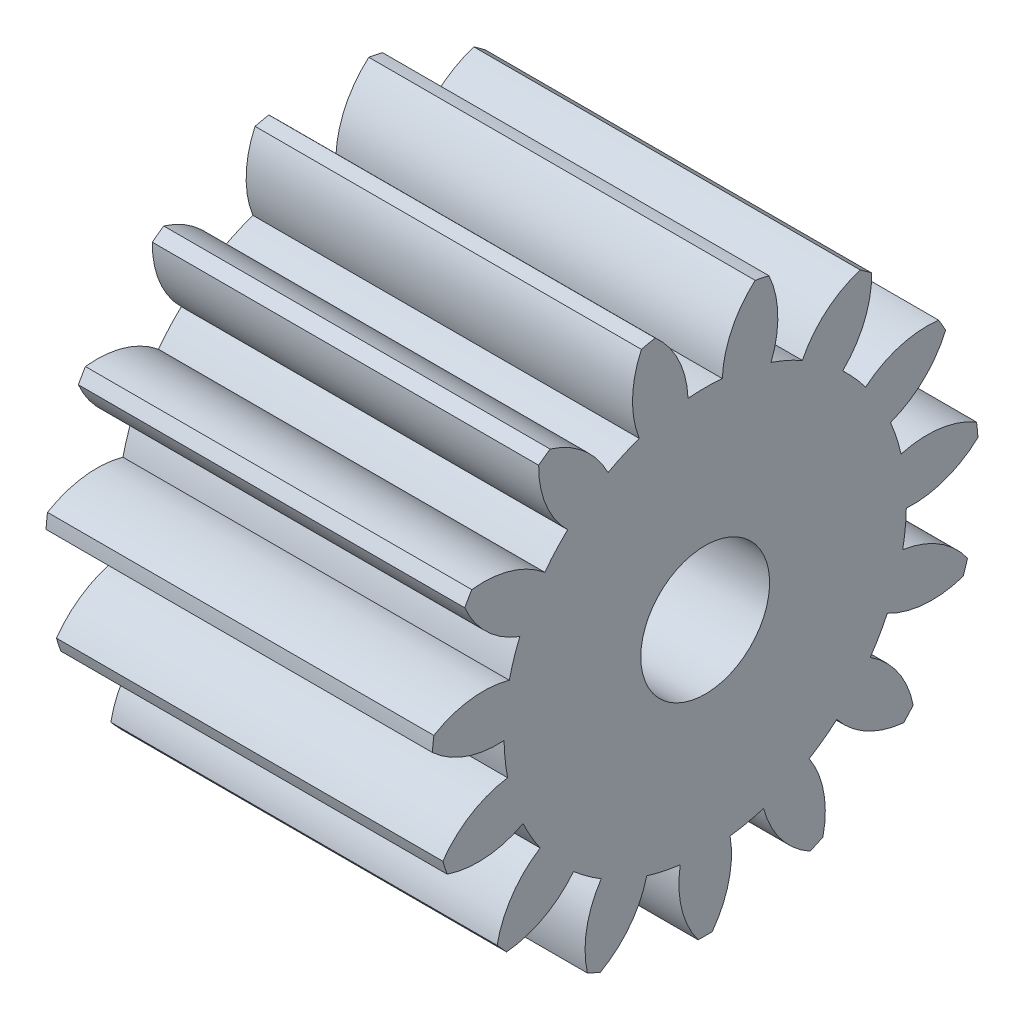
SolidWorks part; units mm, degrees
ref_plane "Plane1" through (0, 0, 0) normal (0, 0, 1) x (1, 0, 0)
ref_plane "Plane2" through (0, 0, 0) normal (0, 1, 0) x (1, 0, 0)
ref_plane "Plane3" through (0, 0, 0) normal (1, 0, 0) x (0, 0, -1)
sketch "HoldingSke" plane through (0, 0, 0) normal (0, 1, 0) x (1, 0, 0)
  line L0 (0, 0) -> (1.9319, -0.5176)
  line L1 (-15, 0) -> (100, 0) construction
  line L2 (0, 0) -> (-2.1039, 2.3779)
  line L3 (0, 0) -> (-11.863, 4.5341)
  line L4 (0, 0) -> (8.3417, 2.2352)
  line L5 (0, 0) -> (-46.8476, -17.4728)
  line L6 (0, 0) -> (-4.9738, -3.3558)
  line L7 (-2.1039, 2.3779) -> (8.6586, 51.2059)
  line L8 (-76.2, 54.61) -> (-75.9, 54.61)
  line L9 (-71.009, 38.7566) -> (-53.1078, 45.2721)
  line L10 (-76.2, 71.12) -> (104.1128, 71.12)
  line L11 (0, 0) -> (-6, 0)
  line L12 (-76.2, 101.6) -> (-76.181, 101.6)
  line L13 (24.9733, 27.94) -> (52.9518, 28.4284)
  line L14 (24.9733, 27.94) -> (24.9743, 27.94)
  line L15 (24.9733, 27.94) -> (100.4006, 29.5858)
  line L16 (-63.627, -0.5) -> (-12.827, -0.5)
  circle A0 centre (0, 0) radius 1
  circle A1 centre (0, 0) radius 3.124
  circle A2 centre (0, 0) radius 37.5
  circle A3 centre (0, 0) radius 1
  dimension "MHD" = 6.248
  dimension "Hub_dia" = 75
  dimension "Bore" = 2
  dimension "MBD" = 2
  dimension "Num_teeth" = 15
  dimension "Pitch" = 2
  dimension "Overall_len" = 50
  dimension "Show_teeth" = 15
  dimension "Thickness" = 6
  dimension "OAL" = 50.0001
  dimension "T_dim" = 0.3
  dimension "Ap" = 20
  dimension "H" = 19.05
  dimension "Pitch_radius" = 180.3128
  dimension "Width" = 6
  dimension "Backlash" = 0.019
  dimension "Addendum_fac" = 1
  dimension "Dedendum_fac" = 1.25
  dimension "Clearance_fac" = 0.25
  dimension "Dedendum_add" = 0.001
  dimension "Module" = 0.5
sketch "BasProSke" plane through (0, 0, 0) normal (0, 1, 0) x (1, 0, 0)
  line L0 (-10, 0) -> (60, 0) construction
  line L1 (0, 0) -> (0, 4.25)
  line L2 (0, 0) -> (6, 0)
  line L3 (6, 0) -> (6, 4.25)
  line L4 (6, 4.25) -> (0, 4.25)
  dimension "Thickness" = 6
  dimension "Diameter" = 8.5
revolve "Base-Revolve" add sketch "BasProSke" angle 360 about L0
sketch "TooCutSke" plane through (0, 0, 0) normal (1, 0, 0) x (0, 0, -1)
  line L1 (0, 0) -> (0, 107) construction
  line L2 (0, 0) -> (-0.4252, 3.7258) construction
  line L3 (0, 0) -> (-1.5522, 7.3025) construction
  line L4 (-0.4252, 3.7258) -> (-0.7761, 3.6512) construction
  arc A0 (0.2658, 3.1127) -> (-0.2658, 3.1127) centre (0, 0) ccw
  arc A1 (0.8008, 4.1997) -> (-0.8008, 4.1997) centre (0, 0) ccw
  circle A2 centre (0, 0) radius 3.75 construction
  circle A3 centre (0, 0) radius 3.5238 construction
  arc A4 (-0.2658, 3.1127) -> (-0.8008, 4.1997) centre (-1.7645, 3.0503) ccw
  arc A5 (0.8008, 4.1997) -> (0.2658, 3.1127) centre (1.7645, 3.0503) ccw
  dimension "Root_dia" = 6.248
  dimension "Overcut_dia" = 8.5508
  dimension "Pitch_dia" = 7.5
  dimension "Base_dia" = 7.0477
  dimension "Flank_rad" = 1.5
  dimension "Half_ang" = 12
  dimension "Half_CT" = 0.3587
extrude "ToothCut" cut sketch "TooCutSke" along normal through all
fillet "Breaks" [suppressed] radius 0.01
fillet "RootFillets" [suppressed] radius 0.126
pattern_circular "TeethCuts" count 15 every 24 about axis through (-10, 0, 0) along (1, 0, 0) of "ToothCut", "RootFillets", "Breaks"
sketch "HubNeaOneSke" plane through (0, 0, 0) normal (-1, 0, 0) x (0, 0, 1)
  circle A0 centre (0, 0) radius 3.124
  dimension "Diameter" = 6.248
extrude "HubNearOne" [suppressed] add sketch "HubNeaOneSke" along normal blind 44.0001
sketch "HubNeaBotSke" plane through (0, 0, 0) normal (-1, 0, 0) x (0, 0, 1)
  circle A0 centre (0, 0) radius 3.124
  dimension "Diameter" = 6.248
extrude "HubNearBoth" [suppressed] add sketch "HubNeaBotSke" along normal blind 22
ref_plane "FarPln" through (6, 0, 0) normal (1, 0, 0) x (0, 0, -1)
sketch "HubFarSke" plane through (6, 0, 0) normal (1, 0, 0) x (0, 0, -1)
  circle A0 centre (0, 0) radius 3.124
  dimension "Diameter" = 6.248
extrude "HubFar" [suppressed] add sketch "HubFarSke" along normal blind 22
sketch "BorSke" plane through (0, 0, 0) normal (1, 0, 0) x (0, 0, -1)
  circle A0 centre (0, 0) radius 1
  dimension "Diameter" = 2
extrude "Bore" cut sketch "BorSke" along normal mid plane 100.0001
sketch "KeySke" plane through (0, 0, 0) normal (1, 0, 0) x (0, 0, -1)
  line L0 (-0.4, 0) -> (-0.4, 1.3)
  line L1 (-0.4, 1.3) -> (0.4, 1.3)
  line L2 (0.4, 1.3) -> (0.4, 0)
  line L3 (0, 0) -> (0, 34) construction
  line L4 (-0.4, 0) -> (0.4, 0)
  dimension "Offset" = 1.3
  dimension "Width" = 0.8
extrude "Keyway" [suppressed] cut sketch "KeySke" along normal mid plane 100.0001
pattern_circular "Keyway2" [suppressed] count 2 every 90 about axis through (-10, 0, 0) along (1, 0, 0)
equation "' \"Module@HoldingSke\" = 6.35"
equation "' \"Num_teeth@HoldingSke\" = 12"
equation "' \"Ap@HoldingSke\" =  20"
equation "' \"Ap@HoldingSke\" = 20"
equation "' \"Width@HoldingSke\" = 0.5 * 25.4"
equation "' \"Hub_dia@HoldingSke\"= 1 * 25.4"
equation "' \"Hub_dia@HoldingSke\" = 1 * 25.4"
equation "' \"Overall_len@HoldingSke\" = 1.0 * 25.4"
equation "' \"Bore@HoldingSke\" = 0.75 * 25.4"
equation "' \"T_dim@HoldingSke\" = 0.1 * 25.4"
equation "' \"Width@KeySke\" = 0.25 * 25.4"
equation "' \"Show_teeth@HoldingSke\" = 13"
equation "' \"Backlash@HoldingSke\" = 0.009 * 25.4"
equation "' \"Addendum_fac@HoldingSke\" = 1.0"
equation "' \"Dedendum_fac@HoldingSke\" = 1.25"
equation "' \"Dedendum_add@HoldingSke\" = 0.00005 * 25.4"
equation "' \"Clearance_fac@HoldingSke\" = 0.25"
equation "\"Pitch@HoldingSke\" = 1 / \"Module@HoldingSke\""
equation "\"Overcut_dia@TooCutSke\" = (\"Num_teeth@HoldingSke\" + 2 * \"Addendum_fac@HoldingSke\") / \"Pitch@HoldingSke\" + 0.002 * 25.4"
equation "\"Pitch_dia@TooCutSke\" = \"Num_teeth@HoldingSke\" / \"Pitch@HoldingSke\""
equation "\"Base_dia@TooCutSke\" = \"Num_teeth@HoldingSke\" / \"Pitch@HoldingSke\" * cos((\"Ap@HoldingSke\"  * 3.14159265 / 180))"
equation "\"Root_dia@TooCutSke\" = (\"Num_teeth@HoldingSke\" + 2) / \"Pitch@HoldingSke\" - 2 * (\"Addendum_fac@HoldingSke\" + \"Dedendum_fac@HoldingSke\") / \"Pitch@HoldingSke\" - \"Dedendum_add@HoldingSke\" * 2"
equation "\"Half_ang@TooCutSke\" = 180 / \"Num_teeth@HoldingSke\""
equation "\"Half_CT@TooCutSke\" = \"Num_teeth@HoldingSke\" / \"Pitch@HoldingSke\" * sin((3.14159265 / 2 / \"Num_teeth@HoldingSke\")) / 2 - 7 * \"Backlash@HoldingSke\" / 4"
equation "\"Flank_rad@TooCutSke\" = \"Num_teeth@HoldingSke\" / \"Pitch@HoldingSke\" / 5"
equation "\"Radius@RootFillets\" = \"Clearance_fac@HoldingSke\" / \"Pitch@HoldingSke\" + \"Dedendum_add@HoldingSke\""
equation "\"Break_rad@Breaks\" = 0.02 / \"Pitch@HoldingSke\""
equation "\"Thickness@HoldingSke\" = \"Width@HoldingSke\""
equation "\"OAL@HoldingSke\" = \"Thickness@HoldingSke\""
equation "\"MHD@HoldingSke\" = (\"Num_teeth@HoldingSke\" + 2) / \"Pitch@HoldingSke\" - 2 * (\"Addendum_fac@HoldingSke\" + \"Dedendum_fac@HoldingSke\")  / \"Pitch@HoldingSke\" - \"Dedendum_add@HoldingSke\" * 2"
equation "\"MBD@HoldingSke\" = (\"Num_teeth@HoldingSke\" + 2) / \"Pitch@HoldingSke\" - 2 * (\"Addendum_fac@HoldingSke\" + \"Dedendum_fac@HoldingSke\")  / \"Pitch@HoldingSke\" - \"Dedendum_add@HoldingSke\" * 2 - 0.002 * 25.4"
equation "\"MHD@HoldingSke\" = ((sgn( \"MHD@HoldingSke\" - \"Hub_dia@HoldingSke\" )-1)*( \"MHD@HoldingSke\" - \"Hub_dia@HoldingSke\" ))/-2+ \"Hub_dia@HoldingSke\""
equation "\"MBD@HoldingSke\" = ((sgn( \"MBD@HoldingSke\" - \"Bore@HoldingSke\" )-1)*( \"MBD@HoldingSke\" - \"Bore@HoldingSke\" ))/-2+ \"Bore@HoldingSke\""
equation "\"OAL@HoldingSke\" = ((sgn( \"OAL@HoldingSke\" - \"Overall_len@HoldingSke\" )+1)*( \"OAL@HoldingSke\" - \"Overall_len@HoldingSke\" ))/2 + \"Overall_len@HoldingSke\" + 0.000002 * 25.4"
equation "\"Num_teeth@TeethCuts\" = int( \"Show_teeth@HoldingSke\" ) + 1"
equation "\"Num_teeth@TeethCuts\" = ((sgn( \"Num_teeth@TeethCuts\" - \"Num_teeth@HoldingSke\" )-1)*( \"Num_teeth@TeethCuts\" - \"Num_teeth@HoldingSke\" ))/-2+ \"Num_teeth@HoldingSke\""
equation "\"Num_teeth@TeethCuts\" = ((sgn( \"Num_teeth@TeethCuts\" - 2.0)+1)*( \"Num_teeth@TeethCuts\" - 2.0))/2 +2.0"
equation "\"Angle@TeethCuts\" = 360.0 / \"Num_teeth@HoldingSke\""
equation "\"Diameter@BasProSke\" = (\"Num_teeth@HoldingSke\" + 2 * \"Addendum_fac@HoldingSke\") / \"Pitch@HoldingSke\""
equation "\"Thickness@BasProSke\"  = \"Thickness@HoldingSke\""
equation "' \"Fillet_rad@BasProSke\" =  \"Thickness@HoldingSke\" * 0.05"
equation "' \"Fillet_rad@BasProSke\" = \"Thickness@HoldingSke\" * 0.05"
equation "\"MHD@HoldingSke\" = ((sgn( \"MHD@HoldingSke\" - \"Root_dia@TooCutSke\" )-1)*( \"MHD@HoldingSke\" - \"Root_dia@TooCutSke\" ))/-2+ \"Root_dia@TooCutSke\""
equation "\"Diameter@HubNeaOneSke\" = \"MHD@HoldingSke\""
equation "\"Length@HubNearOne\" = \"OAL@HoldingSke\" - \"Thickness@BasProSke\""
equation "\"Diameter@HubNeaBotSke\" = \"MHD@HoldingSke\""
equation "\"Length@HubNearBoth\" = ( \"OAL@HoldingSke\" - \"Thickness@BasProSke\" ) / 2.0"
equation "\"Thickness@FarPln\" = \"Thickness@BasProSke\""
equation "\"Diameter@HubFarSke\" = \"MHD@HoldingSke\""
equation "\"Length@HubFar\" = ( \"OAL@HoldingSke\" - \"Thickness@BasProSke\" ) / 2.0"
equation "\"Diameter@BorSke\" = \"MBD@HoldingSke\""
equation "\"D1@Bore\" = \"OAL@HoldingSke\" * 2.0"
equation "\"D1@Keyway\" = \"OAL@HoldingSke\" * 2.0"
equation "\"Offset@KeySke\" = \"T_dim@HoldingSke\" + \"MBD@HoldingSke\" / 2.0"
